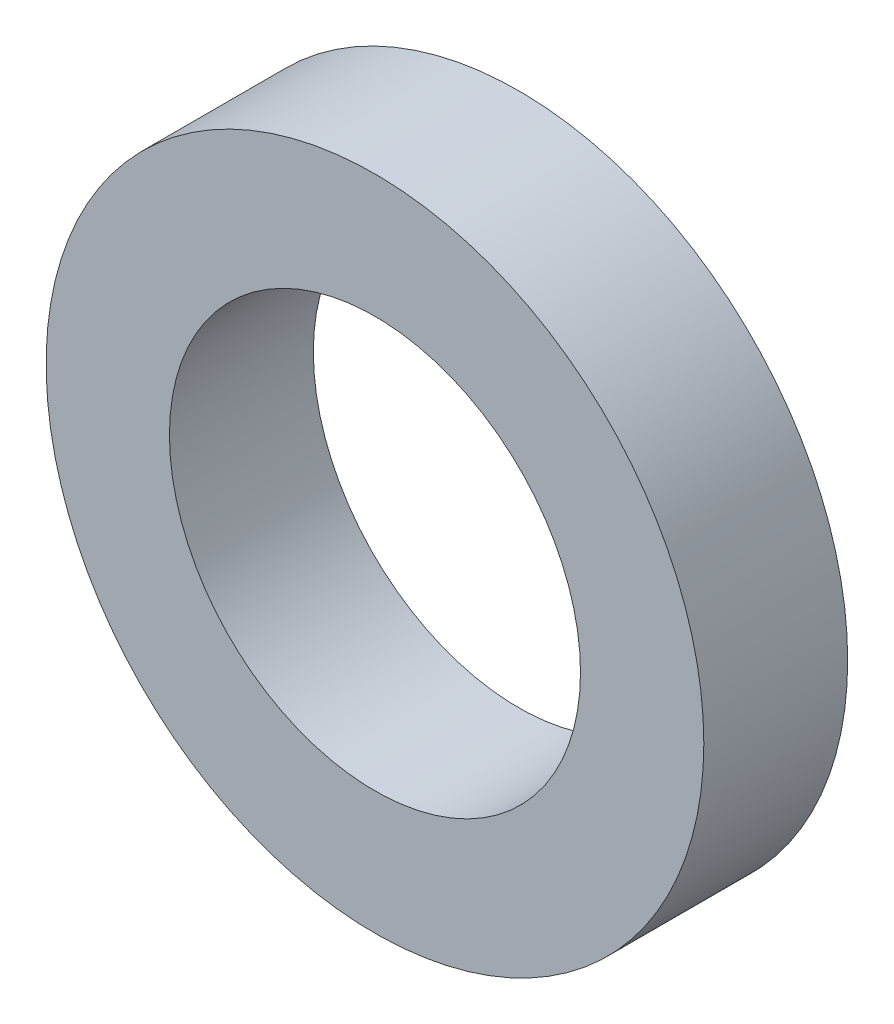
SolidWorks part; units mm, degrees
ref_plane "Front" through (0, 0, 0) normal (0, 0, 1) x (1, 0, 0)
ref_plane "Top" through (0, 0, 0) normal (0, 1, 0) x (1, 0, 0)
ref_plane "Right" through (0, 0, 0) normal (1, 0, 0) x (0, 0, -1)
sketch "Sketch1" plane through (0, 0, 0) normal (0, 0, 1) x (1, 0, 0)
  circle A0 centre (0, 0) radius 16
  circle A1 centre (0, 0) radius 10
  dimension "D1" = 32
  dimension "D2" = 20
extrude "Boss-Extrude1" add sketch "Sketch1" along normal blind 7
